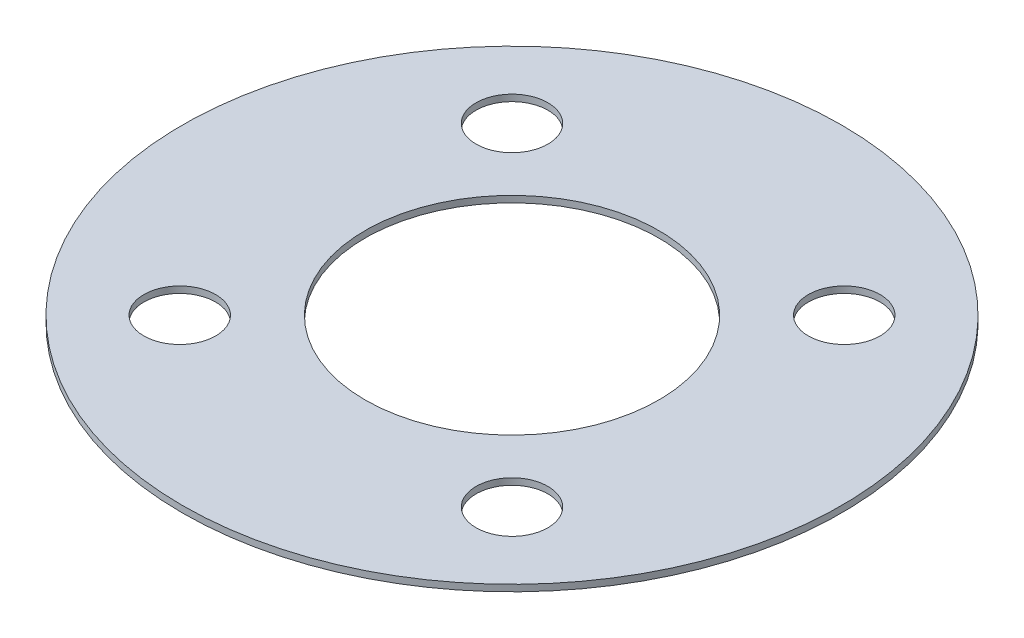
SolidWorks part; units mm, degrees
material "ｼﾘｺﾝ ｺﾞﾑ"
ref_plane "正面" through (0, 0, 0) normal (0, 0, 1) x (1, 0, 0)
ref_plane "平面" through (0, 0, 0) normal (0, 1, 0) x (1, 0, 0)
ref_plane "右側面" through (0, 0, 0) normal (1, 0, 0) x (0, 0, -1)
sketch "ｽｹｯﾁ1" plane through (0, 0, 0) normal (0, 1, 0) x (1, 0, 0)
  circle A0 centre (0, 0) radius 25.25
  dimension "D1" = 50.5
extrude "ﾎﾞｽ - 押し出し1" add sketch "ｽｹｯﾁ1" along normal blind 0.5
sketch "ｽｹｯﾁ2" plane through (0, 0.5, 0) normal (0, 1, 0) x (1, 0, 0)
  circle A0 centre (0, 0) radius 11.25
  dimension "D1" = 22.5
extrude "ｶｯﾄ - 押し出し1" cut sketch "ｽｹｯﾁ2" against normal through all
sketch "ｽｹｯﾁ4" plane through (0, 0.5, 0) normal (0, 1, 0) x (1, 0, 0)
  line L0 (-12.7279, 12.7279) -> (12.7279, -12.7279)
  line L1 (-12.7279, 12.7279) -> (12.7279, 12.7279)
  line L2 (-12.7279, 12.7279) -> (-12.7279, -12.7279)
  line L3 (-12.7279, -12.7279) -> (12.7279, -12.7279)
  line L4 (12.7279, 12.7279) -> (12.7279, -12.7279)
  line L5 (12.7279, 12.7279) -> (-12.7279, -12.7279)
  circle A0 centre (-12.7279, 12.7279) radius 2.5
  circle A1 centre (-12.7279, -12.7279) radius 2.5
  circle A2 centre (12.7279, -12.7279) radius 2.5
  circle A3 centre (12.7279, 12.7279) radius 2.5
  point P0 (-12.7279, 12.7279)
  point P1 (12.7279, -12.7279)
  point P2 (-12.7279, -12.7279)
  point P3 (12.7279, 12.7279)
  point P4 (0, 0)
  dimension "D2" = 5
  dimension "D3" = 5
  dimension "D4" = 5
  dimension "D5" = 5
  dimension "D1" = 18
hole_wizard "M5 すきま穴1" positions "ｽｹｯﾁ4" profile "ｽｹｯﾁ5" hole size "M5" standard "JIS" end condition through all
sketch "ｽｹｯﾁ5" plane through (-12.7279, 0.5, -12.7279) normal (1, 0, 0) x (0, 0, 1)
  line L0 (0, 0) -> (0, 0.5)
  line L1 (0, 0.5) -> (2.75, 0.5)
  line L2 (2.75, 0.5) -> (2.75, 0)
  line L5 (2.75, 0) -> (0, 0)
  line L11 (0, -6.35) -> (0, 107.95) construction
  dimension "通し穴の直径" = 5.5
  dimension "通し穴の深さ" = 0.5
